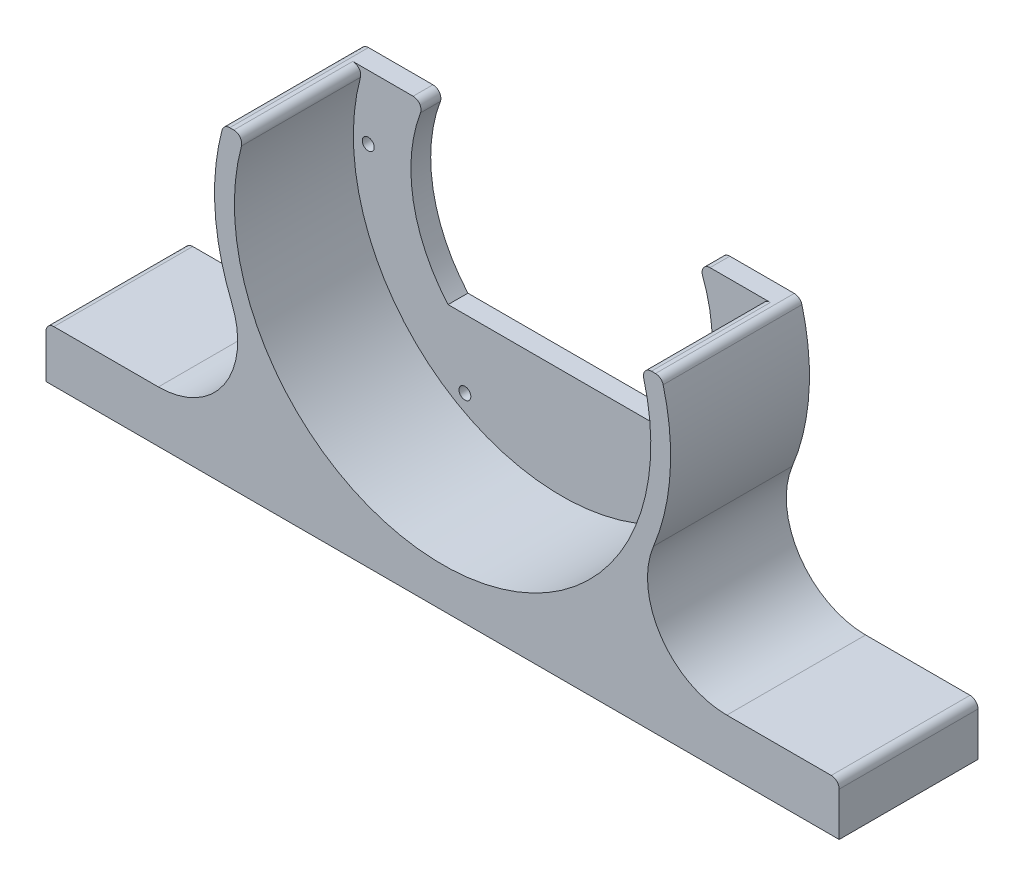
SolidWorks part; units mm, degrees
ref_plane "Front Plane" through (0, 0, 0) normal (0, 0, 1) x (1, 0, 0)
ref_plane "Top Plane" through (0, 0, 0) normal (0, 1, 0) x (1, 0, 0)
ref_plane "Right Plane" through (0, 0, 0) normal (1, 0, 0) x (0, 0, -1)
sketch "Sketch1" plane through (0, 0, 0) normal (0, 0, 1) x (1, 0, 0)
  line L0 (-62.746, -16.0982) -> (65.0304, -16.0982) construction
  line L1 (-49.971, -16.0982) -> (-34.4216, -16.0982)
  line L2 (34.4216, -16.0982) -> (49.971, -16.0982)
  line L3 (28.6182, 25) -> (-28.6182, 25)
  circle A0 centre (0, 0) radius 52.5
  circle A1 centre (0, 0) radius 38
  arc A6 (-50.4872, -1.1347) -> (-50.4872, 1.1347) centre (-48.75, 0) ccw
  arc A7 (-26.2263, 43.1559) -> (-24.2609, 44.2906) centre (-24.375, 42.2187) ccw
  arc A8 (24.2609, 44.2906) -> (26.2263, 43.1559) centre (24.375, 42.2187) ccw
  arc A9 (50.4872, 1.1347) -> (50.4872, -1.1347) centre (48.75, 0) ccw
  dimension "D1" = 76
  dimension "D3" = 105
  dimension "D2" = 25
sketch "Sketch2" plane through (0, 0, 0) normal (0, 0, 1) x (1, 0, 0)
  line L0 (-62.746, -16.0982) -> (65.0304, -16.0982) construction
  line L1 (-49.9704, 16.1) -> (49.9704, 16.1)
  line L2 (28.6182, 25) -> (-28.6182, 25) construction
  line L4 (-28.6182, -25) -> (28.6182, -25)
  circle A0 centre (0, 0) radius 52.5
  circle A1 centre (0, 0) radius 38
  circle A2 centre (0, 0) radius 48.75 construction
  circle A3 centre (-48.75, 0) radius 1.5
  circle A4 centre (-24.375, 42.2187) radius 1.5 [skipped]
  circle A5 centre (24.375, 42.2187) radius 1.5 [skipped]
  circle A6 centre (48.75, 0) radius 1.5
  circle A7 centre (24.375, -42.2187) radius 1.5
  circle A8 centre (-24.375, -42.2187) radius 1.5
  point P30 (0, 0)
  dimension "D1" = 105
  dimension "D2" = 76
  dimension "D3" = 97.5
  dimension "D8" = 3
  dimension "D4" = 16.0982
  dimension "D5" = 16.1
  dimension "D6" = 25
  dimension "D7" = 25
  dimension "D9" = 6
extrude "Boss-Extrude1" add sketch "Sketch2" along normal blind 5 contours A1 L1 A0 A8 A7 A6 A3 | L4 A1
sketch "Sketch4" plane through (0, 0, 0) normal (0, 0, 1) x (1, 0, 0)
  line L0 (-49.9704, 16.1) -> (-34.4208, 16.1) construction
  line L1 (-49.9704, 16.1) -> (-34.4208, 16.1)
  line L2 (-55.2, 16.1) -> (55.2, 16.1)
  arc A0 (-49.9704, 16.1) -> (49.9704, 16.1) centre (0, 0) ccw
  arc A1 (-55.2, 16.1) -> (55.2, 16.1) centre (0, 0) ccw
  dimension "D1" = 115
extrude "Boss-Extrude2" add sketch "Sketch4" along normal blind 35 contours L2 A1 A0
fillet "Fillet1" radius 2 6 edges at (49.9704, 16.1, 20) (-49.9704, 16.1, 20) (55.2, 16.1, 17.5) (-55.2, 16.1, 17.5) (34.4208, 16.1, 2.5) (-34.4208, 16.1, 2.5)
sketch "Sketch5" plane through (0, 0, 0) normal (0, 0, 1) x (1, 0, 0)
  line L0 (100, -57.5) -> (-100, -57.5)
  line L1 (-100, -57.5) -> (-100, -49.5)
  line L2 (-100, -49.5) -> (-29.2575, -49.5)
  line L3 (29.2575, -49.5) -> (100, -49.5)
  line L4 (100, -49.5) -> (100, -57.5)
  line L5 (-100, -57.5) -> (-100, -62.5)
  line L6 (-100, -62.5) -> (100, -62.5)
  line L7 (100, -62.5) -> (100, -57.5)
  arc A1 (-55.6134, 14.6081) -> (55.6134, 14.6081) centre (0, 0) ccw construction
  arc A2 (-55.6134, 14.6081) -> (55.6134, 14.6081) centre (0, 0) ccw construction
  arc A3 (-55.6134, 14.6081) -> (55.6134, 14.6081) centre (0, 0) ccw
  point P3 (0, -57.5)
  dimension "D1" = 8
  dimension "D2" = 200
  dimension "D3" = 5
extrude "Boss-Extrude3" add sketch "Sketch5" along normal up to surface (35 mm away) contours A3 L2 L1 L0 | A3 L0 L4 L3 | L6 L7 L0 L5 up to face at (0, -1.9747, 35)
fillet "Fillet2" radius 20 2 edges at (-29.2575, -49.5, 17.5) (29.2575, -49.5, 17.5)
fillet "Fillet3" radius 2 2 edges at (-100, -49.5, 17.5) (100, -49.5, 17.5)
